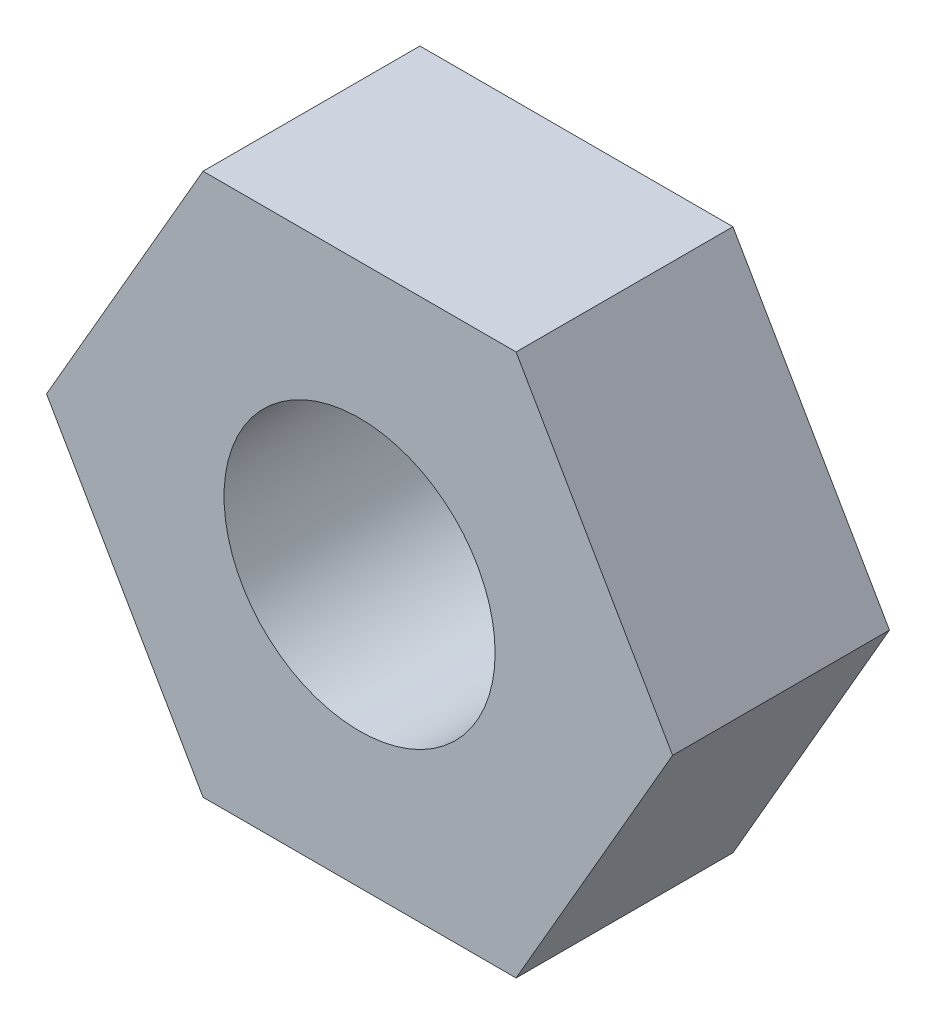
SolidWorks part; units mm, degrees
ref_plane "Front Plane" through (0, 0, 0) normal (0, 0, 1) x (1, 0, 0)
ref_plane "Top Plane" through (0, 0, 0) normal (0, 1, 0) x (1, 0, 0)
ref_plane "Right Plane" through (0, 0, 0) normal (1, 0, 0) x (0, 0, -1)
sketch "Sketch2" plane through (0, 0, 0) normal (0, 0, 1) x (1, 0, 0)
  line L1 (2.3094, 0) -> (1.1547, 2)
  line L2 (1.1547, 2) -> (-1.1547, 2)
  line L3 (-1.1547, 2) -> (-2.3094, 0)
  line L4 (-2.3094, 0) -> (-1.1547, -2)
  line L5 (-1.1547, -2) -> (1.1547, -2)
  line L6 (1.1547, -2) -> (2.3094, 0)
  circle A0 centre (0, 0) radius 2 construction
  dimension "D1" = 4
extrude "Boss-Extrude1" add sketch "Sketch2" along normal blind 1.6
sketch "Sketch3" plane through (0, 0, 1.6) normal (0, 0, 1) x (1, 0, 0)
  circle A0 centre (0, 0) radius 1
  dimension "D1" = 2
extrude "Cut-Extrude1" cut sketch "Sketch3" against normal blind 1.6
